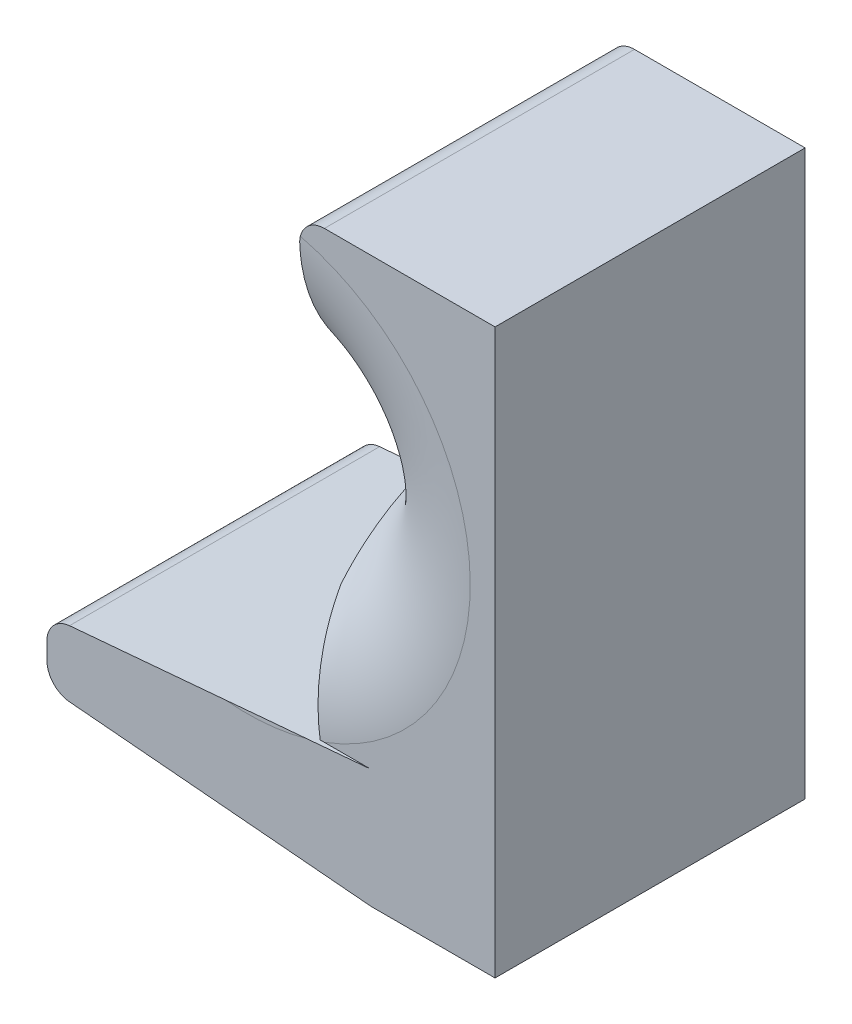
SolidWorks part; units mm, degrees
ref_plane "Front Plane" through (0, 0, 0) normal (0, 0, 1) x (1, 0, 0)
ref_plane "Top Plane" through (0, 0, 0) normal (0, 1, 0) x (1, 0, 0)
ref_plane "Right Plane" through (0, 0, 0) normal (1, 0, 0) x (0, 0, -1)
sketch "finger" plane through (0, 0, 0) normal (0, 0, 1) x (1, 0, 0)
  line L0 (0, 0) -> (5.0161, 13.7815) construction
  line L1 (5.0161, 13.7815) -> (5.0161, 28.518) construction
  line L2 (0, 0) -> (-3.0897, -35.3151)
  line L3 (-3.0897, -35.3151) -> (13.5948, -49.315)
  line L4 (13.5948, -49.315) -> (32.2082, -44.3276)
  line L5 (30.9788, -39.7394) -> (12.3654, -44.7269)
  line L6 (11.136, -40.1387) -> (29.7494, -35.1513)
  line L7 (11.136, -40.1387) -> (12.3654, -44.7269)
  line L8 (12.3654, -44.7269) -> (13.5948, -49.315)
  line L9 (30.9788, -39.7394) -> (35.5669, -38.51) construction
  circle A0 centre (30.9788, -39.7394) radius 4.75
  dimension "D3" = 15
  dimension "D4" = 55
  dimension "D5" = 20
  dimension "D6" = 55
  dimension "D7" = 35.45
  dimension "D8" = 21.78
  dimension "D2" = 9.5
  dimension "D1" = 24.02
ref_plane "est_lift_plane" through (30.9788, 0, 0) normal (1, 0, 0) x (0, 0, -1)
sketch "Sketch5" plane through (0, 0, 0) normal (0, 0, 1) x (1, 0, 0)
  line L0 (0, 1.5) -> (0, 4.5)
  line L1 (0, 4.5) -> (0, 5.5)
  line L2 (0, 1.5) -> (0, 1.6)
  line L3 (0, 1.6) -> (0, 1.65)
  line L4 (4.2426, -3.5) -> (10, -3.5)
  line L5 (0, 0) -> (10, 0)
  line L6 (0, -4.5) -> (10, -4.5)
  line L7 (4.2426, -3.5) -> (4.2426, -4.5)
  line L8 (4.2426, -3.5) -> (4.2426, 12.8193)
  line L10 (4.2426, 12.8193) -> (19.2426, 12.8193)
  line L11 (19.2426, 12.8193) -> (19.2426, -21.9021)
  line L12 (-23.405, -20.4436) -> (10, -21.9021)
  line L13 (-23.405, -20.4436) -> (-23.405, -15.4436)
  line L14 (-23.405, -15.4436) -> (10, -13.9851)
  line L15 (10, -13.9851) -> (10, -4.5)
  line L16 (-19.405, -15.269) -> (-19.405, -20.6183)
  line L17 (-23.405, -17.9436) -> (-19.405, -17.9436)
  line L18 (0, 1.5) -> (0, 1.65)
  line L19 (10, -21.9021) -> (19.2426, -21.9021)
  line L20 (0, 12.8193) -> (0, 10.8193) construction
  circle A0 centre (0, 0) radius 5.5
  circle A1 centre (0, 0) radius 4.5
  circle A2 centre (0, 0) radius 1.5
  circle A3 centre (0, 0) radius 1.6
  circle A4 centre (0, 0) radius 1.65
sketch "Sketch2" plane through (0, 0, 0) normal (0, 0, 1) x (1, 0, 0)
  line L0 (25.7288, -28.9894) -> (25.7288, -25.9894) construction
  line L1 (25.7288, -25.9894) -> (25.7288, -24.9894) construction
  line L2 (25.7288, -28.9894) -> (25.7288, -28.8894) construction
  line L3 (25.7288, -28.8894) -> (25.7288, -28.8394) construction
  line L4 (29.9714, -33.9894) -> (35.7288, -33.9894) construction
  line L5 (25.7288, -30.4894) -> (35.7288, -30.4894) construction
  line L6 (25.7288, -34.9894) -> (35.7288, -34.9894) construction
  line L7 (29.9714, -33.9894) -> (29.9714, -34.9894)
  line L8 (29.9714, -33.9894) -> (29.9714, -11.4894)
  line L9 (29.9714, -11.4894) -> (45.7288, -11.4894)
  line L10 (45.7288, -11.4894) -> (45.7288, -56.9514)
  line L12 (9.5948, -54.665) -> (9.5948, -49.665)
  line L13 (9.5948, -49.665) -> (35.7288, -47.3785)
  line L14 (35.7288, -47.3785) -> (35.7288, -34.9894)
  line L15 (13.5948, -49.315) -> (13.5948, -55.0149)
  line L16 (9.5948, -52.165) -> (13.5948, -52.165)
  line L17 (25.7288, -28.9894) -> (25.7288, -28.8394) construction
  line L18 (-23.405, -20.4436) -> (-23.405, -15.4436) construction
  line L19 (-23.405, -17.9436) -> (-19.405, -17.9436) construction
  line L23 (29.9714, -34.9894) -> (29.9714, -47.4894) construction
  line L24 (25.7288, -30.4894) -> (25.7288, -47.4894) construction
  line L25 (25.7288, -30.4894) -> (25.7288, -13.4894) construction
  line L26 (25.7288, -13.4894) -> (25.7288, -11.4894) construction
  line L28 (29.9714, -34.9894) -> (35.7288, -34.9894)
  line L30 (9.5948, -54.665) -> (35.7288, -56.9514)
  line L34 (35.7288, -56.9514) -> (45.7288, -56.9514)
  line L41 (0, 0) -> (10, 0) construction
  line L42 (4.2426, -3.5) -> (10, -3.5) construction
  line L43 (4.2426, -3.5) -> (4.2426, -4.5) construction
  line L44 (0, 12.8193) -> (0, 10.8193) construction
  circle A0 centre (25.7288, -30.4894) radius 5.5 construction
  circle A1 centre (25.7288, -30.4894) radius 4.5 construction
  circle A2 centre (25.7288, -30.4894) radius 1.5 construction
  circle A3 centre (25.7288, -30.4894) radius 1.6 construction
  circle A4 centre (25.7288, -30.4894) radius 1.65 construction
  circle A6 centre (0, 0) radius 1.5 construction
  circle A7 centre (0, 0) radius 1.65 construction
  circle A9 centre (0, 0) radius 5.5 construction
  circle A10 centre (0, 0) radius 1.6 construction
  circle A12 centre (30.9788, -39.7394) radius 4.75 construction
  dimension "D2" = 5
  dimension "D1" = 12.5
  dimension "D3" = 10
extrude "Boss-Extrude1" add sketch "Sketch2" along normal mid plane 25
sketch "Sketch4" plane through (35.7288, 0, 0) normal (-1, 0, 0) x (0, 0, 1)
  line L0 (0, -38.0236) -> (0, 38.0236) construction
  line L1 (-12.5, -47.4894) -> (-12.5, -34.9894)
  line L2 (-12.5, -34.9894) -> (12.5, -34.9894)
  line L3 (12.5, -34.9894) -> (12.5, -47.4894)
  circle A0 centre (0, -47.4894) radius 12.5 construction
  arc A1 (-12.5, -47.4894) -> (12.5, -47.4894) centre (0, -47.4894) cw
  line M4 (-12.5, -34.9894) -> (-12.5, -47.3785)
  line M6 (12.5, -47.3785) -> (12.5, -34.9894)
  line M7 (12.5, -34.9894) -> (-12.5, -34.9894)
extrude "Boss-Extrude2" add sketch "Sketch4" along normal up to surface (5.7574 mm away) contours A1 L2 M4 | A1 M7 M6
ref_plane "roller_plane" through (25.7288, 0, 0) normal (-1, 0, 0) x (0, 0, 1)
sketch "Sketch3" plane through (25.7288, 0, 0) normal (-1, 0, 0) x (0, 0, 1)
  line L0 (0, -38.0236) -> (0, 38.0236) construction
  line L1 (0, 0) -> (0, -35.3151) construction
  line L2 (-12.5, -30.4894) -> (12.5, -30.4894)
  line L3 (-12.5, -47.3785) -> (-12.5, -11.4894) construction
  line L4 (12.5, -11.4894) -> (12.5, -47.3785) construction
  line L5 (-12.5, -30.4894) -> (-12.5, -12.4894)
  line L6 (12.5, -30.4894) -> (12.5, -12.4894)
  circle A0 centre (0, -12.4894) radius 12.5 construction
  arc A1 (-12.5, -12.4894) -> (12.5, -12.4894) centre (0, -12.4894) ccw
revolve "Cut-Revolve1" cut sketch "Sketch3" angle 360 about L2
fillet "Fillet2" radius 2 3 edges at (29.9714, -11.4894, 0) (9.5948, -49.665, 0) (9.5948, -54.665, 0)
equation "\"depth\"= 9"
equation "\"width\"=25"
equation "\"distal\"= 24.02"
equation "\"proximal\"= 35.45"
equation "\"medial\"= 21.78"
equation "\"D7@finger\" = \"proximal\""
equation "\"D8@finger\" = \"medial\""
equation "\"D1@Boss-Extrude1\"=\"width\""
equation "\"D1@finger\"=\"distal\""
equation "\"D1@Sketch2\"=\"width\"/2"
